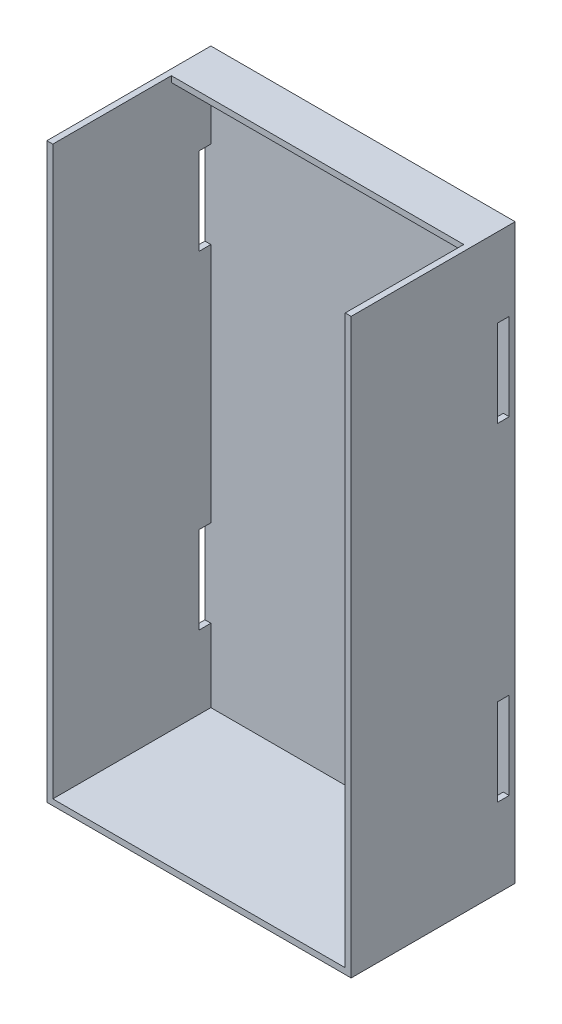
SolidWorks part; units mm, degrees
ref_plane "Спереди" through (0, 0, 0) normal (0, 0, 1) x (1, 0, 0)
ref_plane "Сверху" through (0, 0, 0) normal (0, 1, 0) x (1, 0, 0)
ref_plane "Справа" through (0, 0, 0) normal (1, 0, 0) x (0, 0, -1)
sketch "Эскиз1" plane through (0, 0, 0) normal (0, 0, 1) x (1, 0, 0)
  line L1 (0, 0) -> (77, 0)
  line L2 (0, 0) -> (0, 145)
  line L3 (0, 145) -> (77, 145)
  line L4 (77, 0) -> (77, 145)
  dimension "D1" = 145
  dimension "D2" = 77
extrude "Бобышка-Вытянуть1" add sketch "Эскиз1" along normal blind 1.5
sketch "Эскиз2" plane through (0, 0, 1.5) normal (0, 0, 1) x (1, 0, 0)
  line L0 (1.5, 145) -> (1.5, 1.5)
  line L1 (77, 145) -> (0, 145) construction
  line L2 (75.5, 1.5) -> (75.5, 145)
  line L3 (1.5, 1.5) -> (75.5, 1.5)
  line L4 (0, 0) -> (77, 0) construction
  line L5 (77, 0) -> (77, 145) construction
  line L6 (0, 145) -> (0, 0) construction
  line L7 (1.5, 145) -> (0, 145)
  line L8 (0, 145) -> (0, 0)
  line L9 (0, 0) -> (77, 0)
  line L10 (77, 0) -> (77, 145)
  line L11 (77, 145) -> (75.5, 145)
  dimension "D1" = 1.5
  dimension "D2" = 1.5
  dimension "D3" = 1.5
extrude "Бобышка-Вытянуть2" add sketch "Эскиз2" along normal blind 40
sketch "Эскиз3" plane through (0, 0, 1.5) normal (0, 0, 1) x (1, 0, 0)
  line L0 (1.5, 143.5) -> (75.5, 143.5)
  line L1 (1.5, 1.5) -> (1.5, 145) construction
  line L2 (75.5, 145) -> (75.5, 1.5) construction
  line L3 (75.5, 145) -> (1.5, 145) construction
  line L4 (1.5, 143.5) -> (1.5, 145)
  line L5 (1.5, 145) -> (75.5, 145)
  line L6 (75.5, 145) -> (75.5, 143.5)
  dimension "D1" = 1.5
extrude "Бобышка-Вытянуть3" add sketch "Эскиз3" along normal blind 10
sketch "Эскиз4" plane through (77, 0, 0) normal (1, 0, 0) x (0, 0, -1)
  line L0 (-4.5, 20) -> (-4.5, 0) construction
  line L1 (-4.5, 125) -> (-1.5, 125)
  line L2 (-4.5, 125) -> (-4.5, 103)
  line L3 (-4.5, 103) -> (-1.5, 103)
  line L4 (-1.5, 125) -> (-1.5, 103)
  line L5 (-4.5, 42) -> (-1.5, 42)
  line L6 (-4.5, 42) -> (-4.5, 20)
  line L7 (-4.5, 20) -> (-1.5, 20)
  line L8 (-1.5, 42) -> (-1.5, 20)
  line L9 (-41.5, 0) -> (0, 0) construction
  line L10 (-4.5, 125) -> (-4.5, 145) construction
  line L11 (-41.5, 145) -> (0, 145) construction
  line L12 (0, 0) -> (0, 145) construction
  dimension "D1" = 1.5
  dimension "D2" = 22
  dimension "D3" = 3
  dimension "D4" = 20
extrude "Вырез-Вытянуть1" cut sketch "Эскиз4" against normal blind 100
